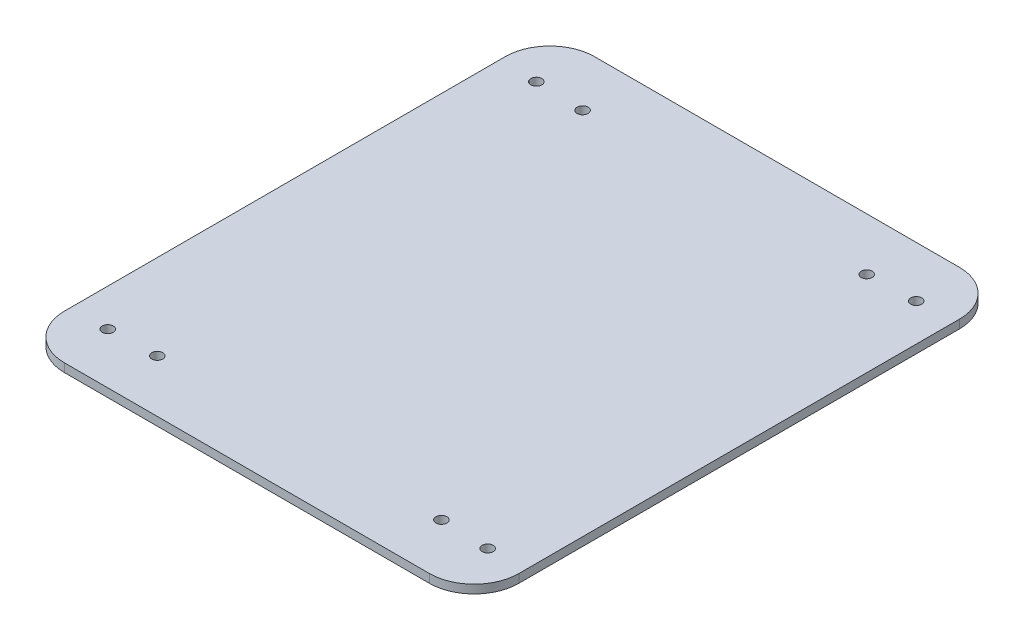
SolidWorks part; units mm, degrees
material "Pine"
ref_plane "Front" through (0, 0, 0) normal (0, 0, 1) x (1, 0, 0)
ref_plane "Top" through (0, 0, 0) normal (0, 1, 0) x (1, 0, 0)
ref_plane "Right" through (0, 0, 0) normal (1, 0, 0) x (0, 0, -1)
sketch "Sketch2" plane through (0, 0, 0) normal (0, 1, 0) x (1, 0, 0)
  line L1 (-76.2, 88.9) -> (76.2, 88.9)
  line L2 (-76.2, 88.9) -> (-76.2, -88.9)
  line L3 (-76.2, -88.9) -> (76.2, -88.9)
  line L4 (76.2, 88.9) -> (76.2, -88.9)
  line L5 (-76.2, 88.9) -> (76.2, -88.9) construction
  line L6 (-76.2, -88.9) -> (76.2, 88.9) construction
  point P0 (0, 0)
  dimension "D1" = 152.4
  dimension "D2" = 177.8
extrude "Boss-Extrude2" add sketch "Sketch2" along normal blind 2.85
sketch "Sketch1" plane through (0, 0, 0) normal (0, 1, 0) x (1, 0, 0)
  line L0 (-50.8, 87.9882) -> (50.8, 87.9882)
  line L1 (50.8, 87.9882) -> (101.6, 0)
  line L2 (101.6, 0) -> (50.8, -87.9882)
  line L3 (50.8, -87.9882) -> (-50.8, -87.9882)
  line L4 (-50.8, -87.9882) -> (-101.6, 0)
  line L5 (-101.6, 0) -> (-50.8, 87.9882)
  line L6 (-101.6, 0) -> (101.6, 0) construction
  line L7 (-50.8, 87.9882) -> (50.8, -87.9882) construction
  dimension "D1" = 203.2
extrude "Cut-Extrude1" cut sketch "Sketch3" against normal through all
sketch "Sketch3" plane through (0, -2, 0) normal (0, -1, 0) x (1, 0, 0)
  circle A0 centre (-63.7, 71.8603) radius 1.85
  circle A1 centre (-47.6336, 71.3056) radius 1.85
mirror "Mirror1" about plane through (0, 0, 0) normal (0, 0, 1) of "Cut-Extrude1"
mirror "Mirror2" about plane through (0, 0, 0) normal (1, 0, 0) of "Mirror1", "Cut-Extrude1"
fillet "Fillet1" radius 15 4 edges at (-76.2, 1.425, -88.9) (76.2, 1.425, -88.9) (76.2, 1.425, 88.9) (-76.2, 1.425, 88.9)
